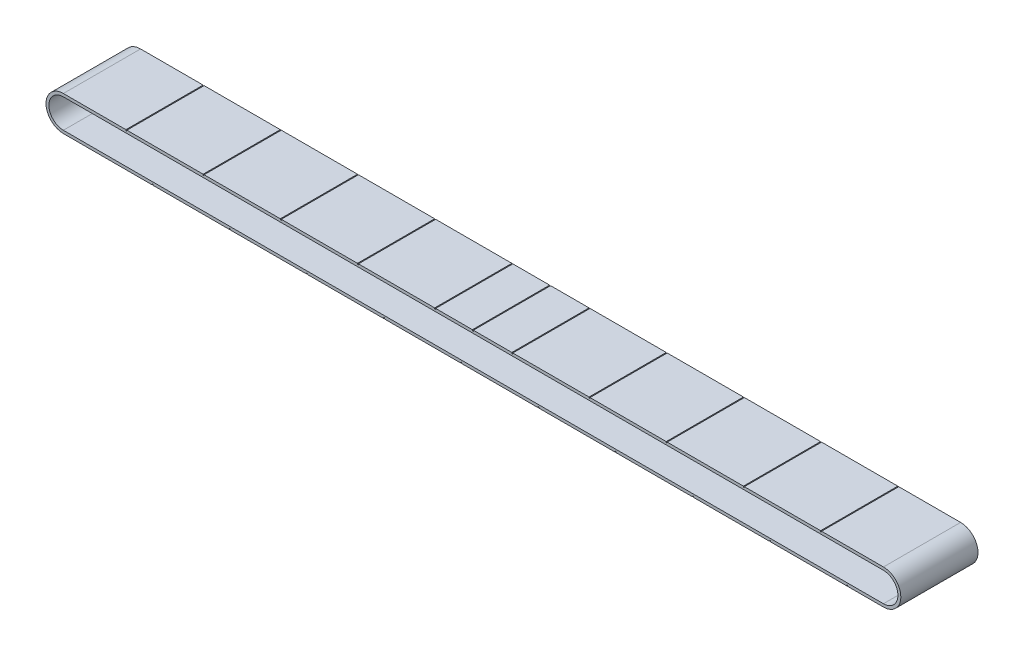
SolidWorks part; units mm, degrees
ref_plane "Alzado" through (0, 0, 0) normal (0, 0, 1) x (1, 0, 0)
ref_plane "Planta" through (0, 0, 0) normal (0, 1, 0) x (1, 0, 0)
ref_plane "Vista lateral" through (0, 0, 0) normal (1, 0, 0) x (0, 0, -1)
sketch "Croquis1" plane through (0, 0, 0) normal (0, 0, 1) x (1, 0, 0)
  line L0 (0, 0) -> (850, 0)
  line L2 (850, -30) -> (0, -30)
  arc A0 (850, -30) -> (850, 0) centre (850, -15) ccw
  arc A1 (0, 0) -> (0, -30) centre (0, -15) ccw
  point P8 (865, -15)
  point P10 (-15, -15)
  dimension "D3" = 880
  dimension "D2" = 30
extrude "Extruir-Lámina1" add sketch "Croquis1" along normal blind 80 thin contours L2 A1 L0 A0 thin type one direction wall 3
sketch "Croquis2" plane through (0, 0, 80) normal (0, 0, 1) x (1, 0, 0)
  line L0 (850, 3) -> (0, 3) construction
  point P0 (14.5615, 3)
sketch "Croquis3" plane through (0, 0, 80) normal (0, 0, 1) x (1, 0, 0)
  line L0 (0, 0) -> (850, 0) construction
  point P0 (24.4682, 0)
sketch "Croquis4" plane through (0, 3, 0) normal (0, 1, 0) x (1, 0, 0)
  line L0 (425, 0) -> (425, -80)
  line L1 (850, 0) -> (0, 0) construction
  line L2 (850, -80) -> (0, -80) construction
  line L3 (65.8745, 0) -> (65.8745, -80)
  line L4 (145.8745, 0) -> (145.8745, -80)
  line L5 (225.8745, 0) -> (225.8745, -80)
  line L6 (305.8745, 0) -> (305.8745, -80)
  line L7 (385.8745, 0) -> (385.8745, -80)
  line L8 (465.8745, 0) -> (465.8745, -80)
  line L9 (545.8745, 0) -> (545.8745, -80)
  line L10 (625.8745, 0) -> (625.8745, -80)
  line L11 (705.8745, 0) -> (705.8745, -80)
  line L12 (785.8745, 0) -> (785.8745, -80)
  dimension "D1" = 10
extrude "Cortar-Extruir-Lámina1" cut sketch "Croquis4" against normal blind 1 thin
sketch "Croquis5" plane through (0, -33, 0) normal (0, -1, 0) x (1, 0, 0)
  line L0 (92.9092, 80) -> (92.9092, 0)
  line L1 (0, 80) -> (850, 80) construction
  line L2 (0, 0) -> (850, 0) construction
  line L3 (172.9092, 80) -> (172.9092, 0)
  line L4 (252.9092, 80) -> (252.9092, 0)
  line L5 (332.9092, 80) -> (332.9092, 0)
  line L6 (412.9092, 80) -> (412.9092, 0)
  line L7 (492.9092, 80) -> (492.9092, 0)
  line L8 (572.9092, 80) -> (572.9092, 0)
  line L9 (652.9092, 80) -> (652.9092, 0)
  line L10 (732.9092, 80) -> (732.9092, 0)
  line L11 (812.9092, 80) -> (812.9092, 0)
  dimension "D1" = 10
extrude "Cortar-Extruir-Lámina2" cut sketch "Croquis5" against normal blind 1 thin
